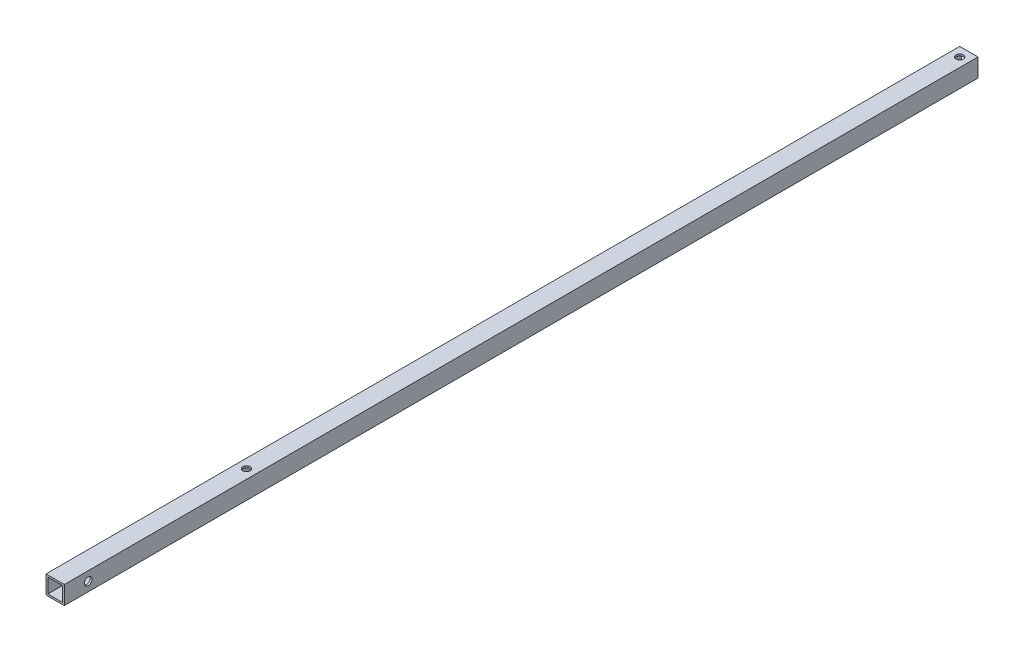
SolidWorks part; units mm, degrees
material "1060 合金"
ref_plane "正面" through (0, 0, 0) normal (0, 0, 1) x (1, 0, 0)
ref_plane "平面" through (0, 0, 0) normal (0, 1, 0) x (1, 0, 0)
ref_plane "右側面" through (0, 0, 0) normal (1, 0, 0) x (0, 0, -1)
sketch "ｽｹｯﾁ1" plane through (0, 0, 0) normal (0, 0, 1) x (1, 0, 0)
  line L1 (-5, -5) -> (5, -5)
  line L2 (-5, -5) -> (-5, 5)
  line L3 (-5, 5) -> (5, 5)
  line L4 (5, -5) -> (5, 5)
  line L5 (-5, -5) -> (5, 5) construction
  line L6 (-5, 5) -> (5, -5) construction
  point P0 (0, 0)
  dimension "D1" = 10
extrude "押し出し-薄板1" add sketch "ｽｹｯﾁ1" along normal blind 499 thin thin type one direction reverse wall 1
sketch "ｽｹｯﾁ2" plane through (0, 5, 0) normal (0, 1, 0) x (1, 0, 0)
  line L0 (0, 0) -> (0, -499) construction
  line L1 (5, -499) -> (-5, -499) construction
  line L2 (5, 0) -> (-5, 0) construction
  circle A0 centre (0, -5) radius 2
  circle A1 centre (0, -394.5) radius 2
  dimension "D1" = 5
  dimension "D2" = 389.5
  dimension "D3" = 4
extrude "ｶｯﾄ - 押し出し1" cut sketch "ｽｹｯﾁ2" against normal through all
sketch "ｽｹｯﾁ3" plane through (5, 0, 0) normal (1, 0, 0) x (0, 0, -1)
  line L0 (0, 0) -> (50000, 0) construction
  line L1 (0, -5) -> (0, 5) construction
  circle A0 centre (-485.96, 0) radius 2.1
  dimension "D1" = 485.96
  dimension "D2" = 4.2
extrude "ｶｯﾄ - 押し出し2" cut sketch "ｽｹｯﾁ3" against normal through all
